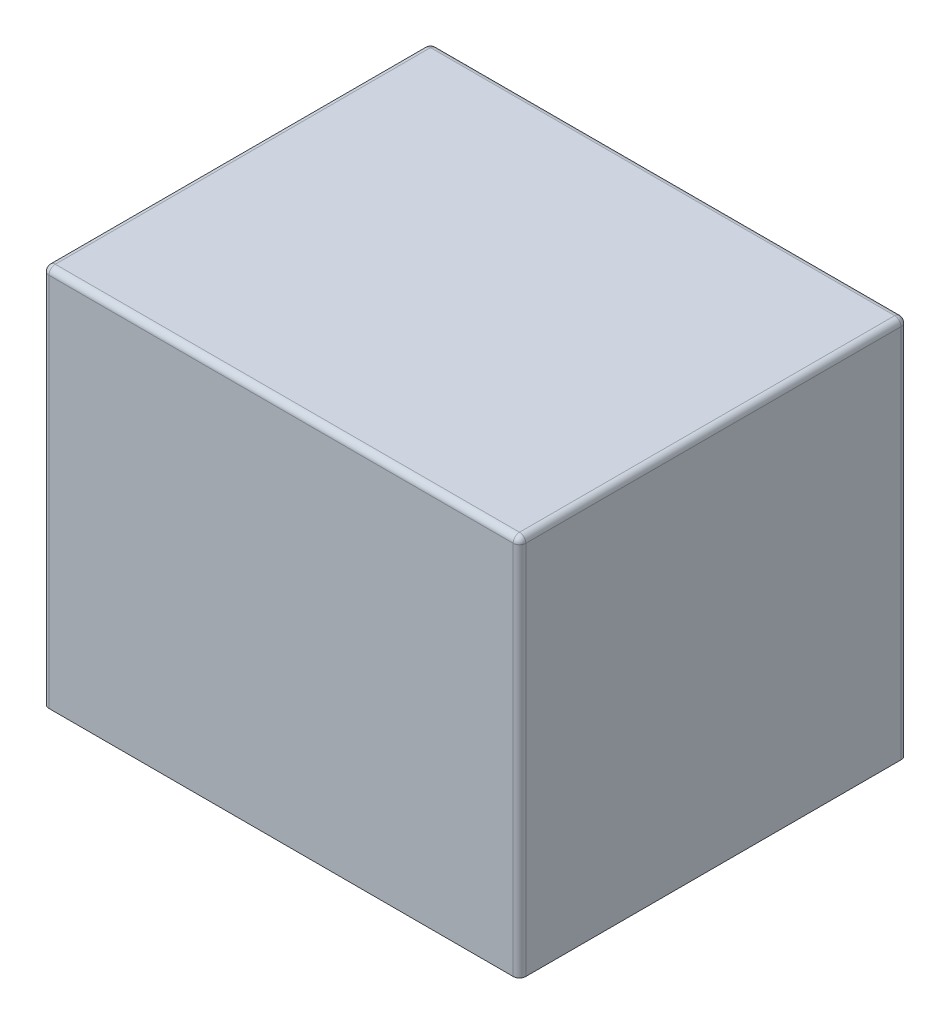
SolidWorks part; units mm, degrees
ref_plane "前视基准面" through (0, 0, 0) normal (0, 0, 1) x (1, 0, 0)
ref_plane "上视基准面" through (0, 0, 0) normal (0, 1, 0) x (1, 0, 0)
ref_plane "右视基准面" through (0, 0, 0) normal (1, 0, 0) x (0, 0, -1)
sketch "草图1" plane through (0, 0, 0) normal (0, 0, 1) x (1, 0, 0)
  line L1 (0, 0) -> (19.05, 0)
  line L2 (0, 0) -> (0, 15.24)
  line L3 (0, 15.24) -> (19.05, 15.24)
  line L4 (19.05, 0) -> (19.05, 15.24)
extrude "凸台-拉伸1" add sketch "草图1" against normal blind 15.494
fillet "圆角1" radius 0.254 8 edges at (0, 7.62, 0) (0, 15.24, -7.747) (0, 7.62, -15.494) (9.525, 15.24, -15.494) (19.05, 7.62, -15.494) (19.05, 15.24, -7.747) (19.05, 7.62, 0) (9.525, 15.24, 0)
